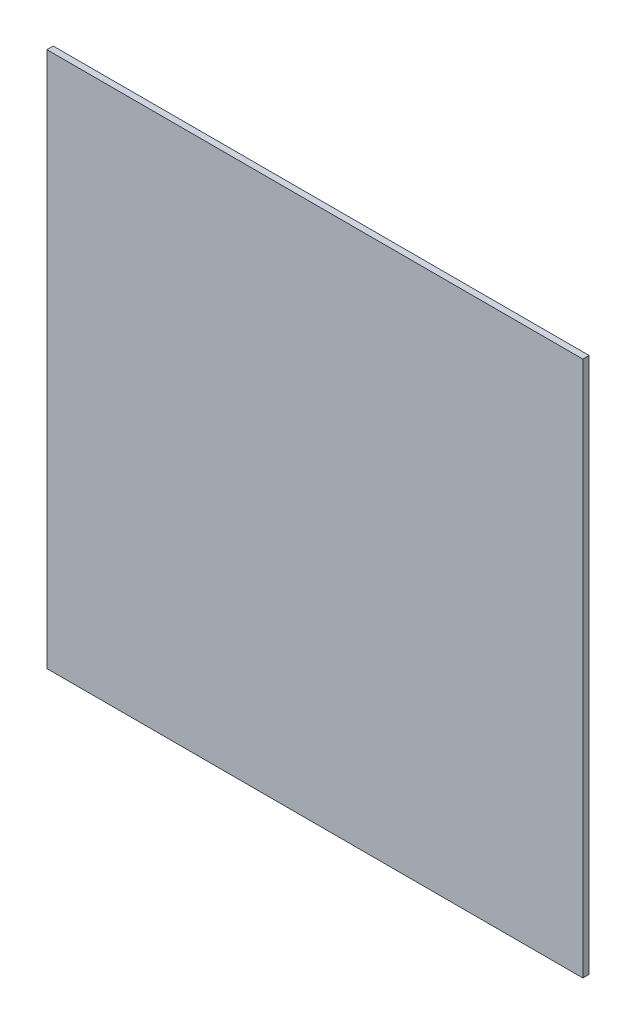
SolidWorks part; units mm, degrees
material "5052-O"
ref_plane "Front Plane" through (0, 0, 0) normal (0, 0, 1) x (1, 0, 0)
ref_plane "Top Plane" through (0, 0, 0) normal (0, 1, 0) x (1, 0, 0)
ref_plane "Right Plane" through (0, 0, 0) normal (1, 0, 0) x (0, 0, -1)
sketch "Sketch2" plane through (0, 0, 0) normal (0, 0, 1) x (1, 0, 0)
  line L1 (-170, 170) -> (170, 170)
  line L2 (-170, 170) -> (-170, -170)
  line L3 (-170, -170) -> (170, -170)
  line L4 (170, 170) -> (170, -170)
  dimension "D1" = 340
  dimension "D2" = 340
  dimension "D3" = 170
  dimension "D4" = 170
extrude "Boss-Extrude2" add sketch "Sketch2" along normal blind 4
